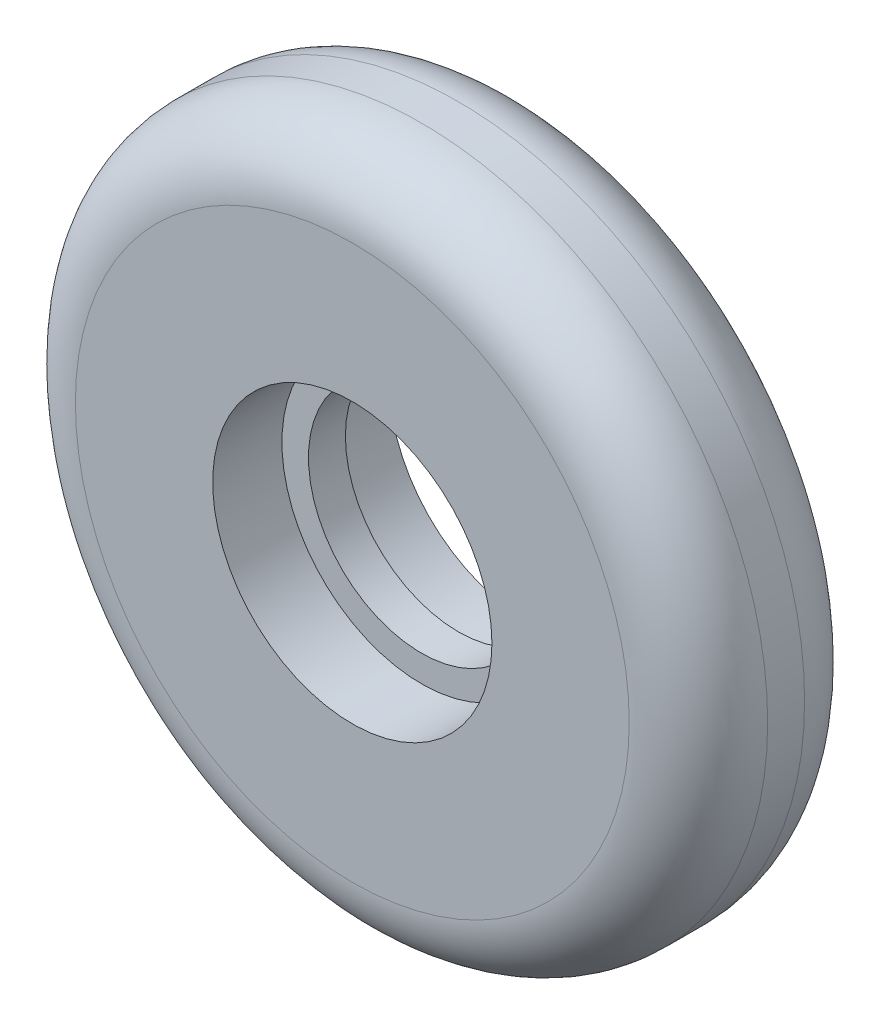
SolidWorks part; units mm, degrees
ref_plane "前视基准面" through (0, 0, 0) normal (0, 0, 1) x (1, 0, 0)
ref_plane "上视基准面" through (0, 0, 0) normal (0, 1, 0) x (1, 0, 0)
ref_plane "右视基准面" through (0, 0, 0) normal (1, 0, 0) x (0, 0, -1)
sketch "草图1" plane through (0, 0, 0) normal (0, 0, 1) x (1, 0, 0)
  circle A0 centre (0, 0) radius 15
  dimension "D1" = 30
extrude "凸台-拉伸1" add sketch "草图1" along normal blind 7.6
sketch "草图2" plane through (0, 0, 7.6) normal (0, 0, 1) x (1, 0, 0)
  circle A0 centre (0, 0) radius 6.05
  dimension "D1" = 12.1
extrude "切除-拉伸1" cut sketch "草图2" against normal blind 3
sketch "草图3" plane through (0, 0, 0) normal (0, 0, -1) x (-1, 0, 0)
  circle A0 centre (0, 0) radius 6
  dimension "D1" = 12
extrude "切除-拉伸2" cut sketch "草图3" against normal blind 3
sketch "草图4" plane through (0, 0, 4.6) normal (0, 0, 1) x (1, 0, 0)
  circle A0 centre (0, 0) radius 4.9
  dimension "D1" = 9.8
extrude "切除-拉伸3" cut sketch "草图4" against normal through all
fillet "圆角1" radius 3 2 edges at (15, 0, 0) (15, 0, 7.6)
